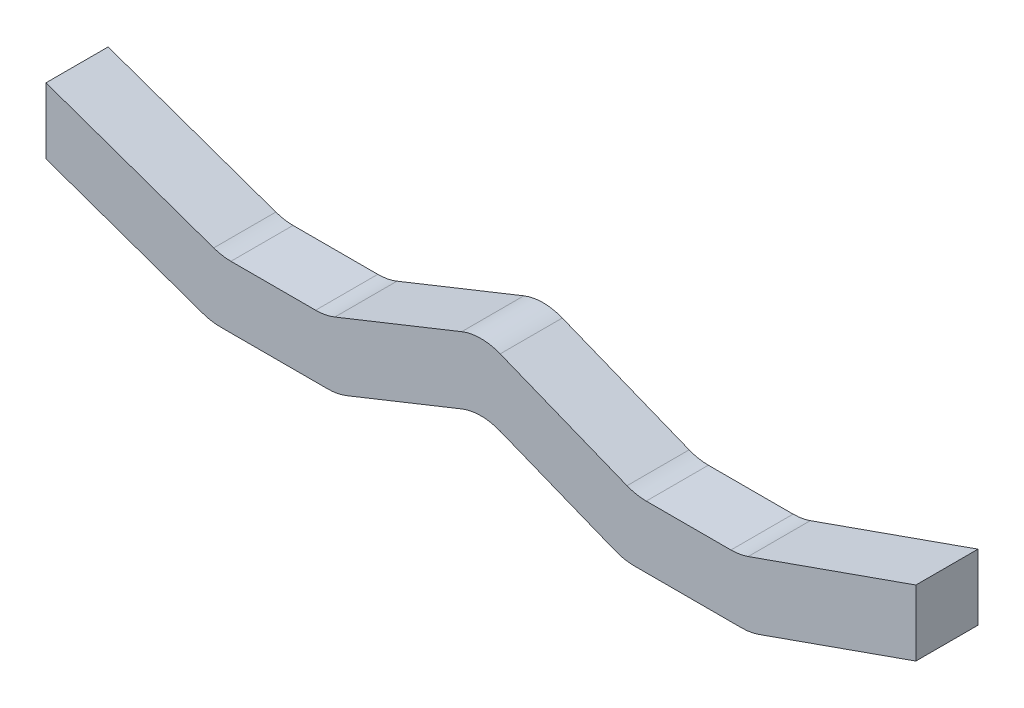
SolidWorks part; units mm, degrees
material "Pine"
ref_plane "Front Plane" through (0, 0, 0) normal (0, 0, 1) x (1, 0, 0)
ref_plane "Top Plane" through (0, 0, 0) normal (0, 1, 0) x (1, 0, 0)
ref_plane "Right Plane" through (0, 0, 0) normal (1, 0, 0) x (0, 0, -1)
sketch "Sketch1" plane through (0, 0, 0) normal (0, 0, 1) x (1, 0, 0)
  line L17 (0, -1000) -> (0, 49000) construction
  line L27 (0, 0) -> (47.625, -19.05)
  line L28 (47.625, -19.05) -> (79.375, -19.05)
  line L30 (79.375, -19.05) -> (133.35, 0)
  line L37 (133.35, 0) -> (133.35, -20.2017)
  line L38 (133.35, -20.2017) -> (82.6381, -38.1)
  line L39 (82.6381, -38.1) -> (43.9563, -38.1)
  line L40 (43.9563, -38.1) -> (0, -20.5175)
  line L42 (-43.9563, -38.1) -> (0, -20.5175)
  line L43 (-82.6381, -38.1) -> (-43.9563, -38.1)
  line L44 (-133.35, -20.2017) -> (-82.6381, -38.1)
  line L45 (-133.35, 0) -> (-133.35, -20.2017)
  line L46 (-79.375, -19.05) -> (-133.35, 0)
  line L47 (-47.625, -19.05) -> (-79.375, -19.05)
  line L48 (0, 0) -> (-47.625, -19.05)
  point P14 (63.5, -19.05)
  dimension "D1" = 31.75
  dimension "D2" = 266.7
  dimension "D3" = 19.05
  dimension "D4" = 19.05
  dimension "D5" = 19.05
  dimension "D6" = 63.5
  dimension "D7" = 19.05
extrude "Boss-Extrude1" add sketch "Sketch1" along normal blind 19.05
fillet "Fillet1" radius 15.875 10 edges at (79.375, -19.05, 9.525) (47.625, -19.05, 9.525) (82.6381, -38.1, 9.525) (43.9563, -38.1, 9.525) (0, -20.5175, 9.525) (-43.9563, -38.1, 9.525) (-82.6381, -38.1, 9.525) (-79.375, -19.05, 9.525) (-47.625, -19.05, 9.525) (0, 0, 9.525)
ref_plane "Plane1" through (-63.669, 0, 0) normal (-1, 0, 0) x (0, 0, 1)
